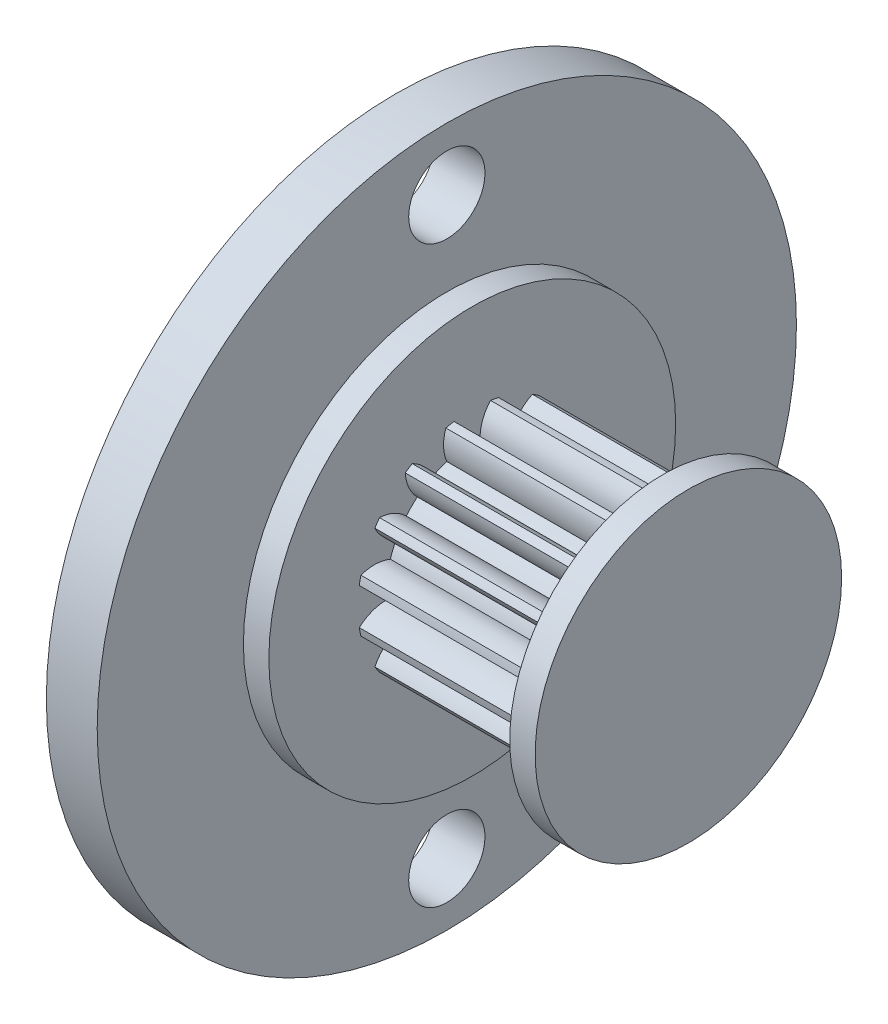
SolidWorks part; units mm, degrees
ref_plane "Plane1" through (0, 0, 0) normal (0, 0, 1) x (1, 0, 0)
ref_plane "Plane2" through (0, 0, 0) normal (0, 1, 0) x (1, 0, 0)
ref_plane "Plane3" through (0, 0, 0) normal (1, 0, 0) x (0, 0, -1)
sketch "HoldingSke" plane through (0, 0, 0) normal (0, 1, 0) x (1, 0, 0)
  line L0 (0, 0) -> (1.9225, -0.5513)
  line L1 (-15, 0) -> (100, 0) construction
  line L2 (0, 0) -> (-2.1039, 2.3779)
  line L3 (0, 0) -> (-11.863, 4.5341)
  line L4 (0, 0) -> (8.3015, 2.3804)
  line L5 (0, 0) -> (-46.8476, -17.4728)
  line L6 (0, 0) -> (-6.2172, -4.1948)
  line L7 (-2.1039, 2.3779) -> (8.6586, 51.2059)
  line L8 (-76.2, 54.61) -> (-75.3, 54.61)
  line L9 (-67.7845, 28.3722) -> (-49.3413, 33.142)
  line L10 (-76.2, 71.12) -> (104.1128, 71.12)
  line L11 (0, 0) -> (-7.5, 0)
  line L12 (-76.2, 101.6) -> (-76.181, 101.6)
  line L13 (24.9733, 27.94) -> (52.9518, 28.4284)
  line L14 (24.9733, 27.94) -> (24.9743, 27.94)
  line L15 (24.9733, 27.94) -> (100.4006, 29.5858)
  line L16 (-63.627, -0.5) -> (-12.827, -0.5)
  circle A0 centre (0, 0) radius 2.5
  circle A1 centre (0, 0) radius 3.374
  circle A2 centre (0, 0) radius 37.5
  circle A3 centre (0, 0) radius 2.5
  dimension "MHD" = 6.748
  dimension "Hub_dia" = 75
  dimension "Bore" = 5
  dimension "MBD" = 5
  dimension "Num_teeth" = 16
  dimension "Pitch" = 2
  dimension "Overall_len" = 50
  dimension "Show_teeth" = 16
  dimension "Thickness" = 7.5
  dimension "OAL" = 50.0001
  dimension "T_dim" = 0.9
  dimension "Ap" = 14.5
  dimension "H" = 19.05
  dimension "Pitch_radius" = 180.3128
  dimension "Width" = 7.5
  dimension "Backlash" = 0.019
  dimension "Addendum_fac" = 1
  dimension "Dedendum_fac" = 1.25
  dimension "Clearance_fac" = 0.25
  dimension "Dedendum_add" = 0.001
  dimension "Module" = 0.5
sketch "BasProSke" plane through (0, 0, 0) normal (0, 1, 0) x (1, 0, 0)
  line L0 (-10, 0) -> (60, 0) construction
  line L1 (0, 0) -> (0, 4.5)
  line L2 (0, 0) -> (7.5, 0)
  line L3 (7.5, 0) -> (7.5, 4.5)
  line L4 (7.5, 4.5) -> (0, 4.5)
  dimension "Thickness" = 7.5
  dimension "Diameter" = 9
revolve "Base-Revolve" add sketch "BasProSke" angle 360 about L0
sketch "TooCutSke" plane through (0, 0, 0) normal (1, 0, 0) x (0, 0, -1)
  line L1 (0, 0) -> (0, 107) construction
  line L2 (0, 0) -> (-0.4253, 3.9773) construction
  line L3 (0, 0) -> (-1.5544, 7.8146) construction
  line L4 (-0.4253, 3.9773) -> (-0.7772, 3.9073) construction
  arc A0 (0.306, 3.3601) -> (-0.306, 3.3601) centre (0, 0) ccw
  arc A1 (0.7382, 4.4648) -> (-0.7382, 4.4648) centre (0, 0) ccw
  circle A2 centre (0, 0) radius 4 construction
  circle A3 centre (0, 0) radius 3.8726 construction
  arc A4 (-0.306, 3.3601) -> (-0.7382, 4.4648) centre (-1.906, 3.3711) ccw
  arc A5 (0.7382, 4.4648) -> (0.306, 3.3601) centre (1.906, 3.3711) ccw
  dimension "Root_dia" = 6.748
  dimension "Overcut_dia" = 9.0508
  dimension "Pitch_dia" = 8
  dimension "Base_dia" = 7.7452
  dimension "Flank_rad" = 1.6
  dimension "Half_ang" = 11.25
  dimension "Half_CT" = 0.3588
extrude "ToothCut" cut sketch "TooCutSke" along normal through all
fillet "Breaks" [suppressed] radius 0.01
fillet "RootFillets" [suppressed] radius 0.126
pattern_circular "TeethCuts" count 16 every 22.5 about axis through (-10, 0, 0) along (1, 0, 0) of "ToothCut", "RootFillets", "Breaks"
sketch "HubNeaOneSke" plane through (0, 0, 0) normal (-1, 0, 0) x (0, 0, 1)
  circle A0 centre (0, 0) radius 3.374
  dimension "Diameter" = 6.748
extrude "HubNearOne" [suppressed] add sketch "HubNeaOneSke" along normal blind 42.5001
sketch "HubNeaBotSke" plane through (0, 0, 0) normal (-1, 0, 0) x (0, 0, 1)
  circle A0 centre (0, 0) radius 3.374
  dimension "Diameter" = 6.748
extrude "HubNearBoth" [suppressed] add sketch "HubNeaBotSke" along normal blind 21.25
ref_plane "FarPln" through (7.5, 0, 0) normal (1, 0, 0) x (0, 0, -1)
sketch "HubFarSke" plane through (7.5, 0, 0) normal (1, 0, 0) x (0, 0, -1)
  circle A0 centre (0, 0) radius 3.374
  dimension "Diameter" = 6.748
extrude "HubFar" [suppressed] add sketch "HubFarSke" along normal blind 21.25
sketch "BorSke" plane through (0, 0, 0) normal (1, 0, 0) x (0, 0, -1)
  circle A0 centre (0, 0) radius 2.5
  dimension "Diameter" = 5
extrude "Bore" cut sketch "BorSke" along normal mid plane 100.0001
sketch "KeySke" plane through (0, 0, 0) normal (1, 0, 0) x (0, 0, -1)
  line L0 (-1, 0) -> (-1, 3.4)
  line L1 (-1, 3.4) -> (1, 3.4)
  line L2 (1, 3.4) -> (1, 0)
  line L3 (0, 0) -> (0, 34) construction
  line L4 (-1, 0) -> (1, 0)
  dimension "Offset" = 3.4
  dimension "Width" = 2
extrude "Keyway" [suppressed] cut sketch "KeySke" along normal mid plane 100.0001
pattern_circular "Keyway2" [suppressed] count 2 every 90 about axis through (-10, 0, 0) along (1, 0, 0)
sketch "Esquisse4" plane through (0, 0, 0) normal (-1, 0, 0) x (0, 0, 1)
  circle A1 centre (0, 0) radius 6
  dimension "D1" = 12
extrude "Boss.-Extru.3" add sketch "Esquisse4" along normal blind 1
sketch "Esquisse5" plane through (7.5, 0, 0) normal (1, 0, 0) x (0, 0, -1)
  circle A0 centre (0, 0) radius 2.85
  circle A1 centre (0, 0) radius 6.0278
extrude "Boss.-Extru.4" add sketch "Esquisse5" along normal blind 1
sketch "Esquisse7" plane through (0, 0, 0) normal (1, 0, 0) x (0, 0, -1)
  circle A0 centre (0, 0) radius 3.0071
extrude "Boss.-Extru.6" add sketch "Esquisse7" along normal up to surface (8.5 mm away) up to face at (8.5, 0, -6.0278)
sketch "Esquisse9" plane through (-1, 0, 0) normal (-1, 0, 0) x (0, 0, 1)
  circle A0 centre (0, 0) radius 13.75
  circle A1 centre (0, 0) radius 5.5
  dimension "D1" = 27.5
  dimension "D2" = 11
extrude "Boss.-Extru.8" add sketch "Esquisse9" along normal blind 2
sketch "Esquisse10" plane through (-3, 0, 0) normal (-1, 0, 0) x (0, 0, 1)
  line L0 (-13.75, 0) -> (13.75, 0) construction
  line L1 (0, 13.75) -> (0, -13.75) construction
  circle A0 centre (0, 11.3) radius 1.5
  circle A1 centre (0, -11.3) radius 1.5
  circle A2 centre (0, 0) radius 13.75 construction
  dimension "D1" = 0
  dimension "D2" = 3
  dimension "D3" = 11.3
  dimension "D4" = 3
  dimension "D5" = 11.3
  dimension "D6" = 0
extrude "Enlèv. mat.-Extru.3" cut sketch "Esquisse10" against normal through all
sketch "Esquisse11" plane through (-1, 0, 0) normal (-1, 0, 0) x (0, 0, 1)
  circle A0 centre (0, 0) radius 3
  dimension "D1" = 6
extrude "Enlèv. mat.-Extru.4" cut sketch "Esquisse11" against normal blind 4
sketch "Esquisse12" plane through (3, 0, 0) normal (-1, 0, 0) x (0, 0, 1)
  circle A0 centre (0, 0) radius 3
extrude "Boss.-Extru.9" add sketch "Esquisse12" along normal up to surface (4 mm away) up to face at (-1, 0, 3)
sketch "Esquisse13" plane through (-1, 0, 0) normal (-1, 0, 0) x (0, 0, 1)
  circle A0 centre (0, 0) radius 5.5
extrude "Boss.-Extru.10" add sketch "Esquisse13" along normal up to surface (2 mm away) up to face at (-3, 11.3, 1.5)
sketch "Esquisse16" plane through (-1, 0, 0) normal (1, 0, 0) x (0, 0, -1)
  circle A0 centre (0, 0) radius 8
  dimension "D1" = 16
extrude "Boss.-Extru.11" add sketch "Esquisse16" along normal up to surface (1 mm away) up to face at (0, 0, 6)
sketch "Esquisse14" plane through (-3, 0, 0) normal (-1, 0, 0) x (0, 0, 1)
  circle A0 centre (0, 0) radius 6
  dimension "D1" = 12
extrude "Enlèv. mat.-Extru.5" cut sketch "Esquisse14" against normal blind 1.5
sketch "Esquisse15" plane through (-1.5, 0, 0) normal (-1, 0, 0) x (0, 0, 1)
  circle A0 centre (0, 0) radius 3.25
  dimension "D1" = 6.5
extrude "Enlèv. mat.-Extru.6" cut sketch "Esquisse15" against normal blind 4.5
equation "' \"Module@HoldingSke\" = 6.35"
equation "' \"Num_teeth@HoldingSke\" = 12"
equation "' \"Ap@HoldingSke\" =  20"
equation "' \"Ap@HoldingSke\" = 20"
equation "' \"Width@HoldingSke\" = 0.5 * 25.4"
equation "' \"Hub_dia@HoldingSke\"= 1 * 25.4"
equation "' \"Hub_dia@HoldingSke\" = 1 * 25.4"
equation "' \"Overall_len@HoldingSke\" = 1.0 * 25.4"
equation "' \"Bore@HoldingSke\" = 0.75 * 25.4"
equation "' \"T_dim@HoldingSke\" = 0.1 * 25.4"
equation "' \"Width@KeySke\" = 0.25 * 25.4"
equation "' \"Show_teeth@HoldingSke\" = 13"
equation "' \"Backlash@HoldingSke\" = 0.009 * 25.4"
equation "' \"Addendum_fac@HoldingSke\" = 1.0"
equation "' \"Dedendum_fac@HoldingSke\" = 1.25"
equation "' \"Dedendum_add@HoldingSke\" = 0.00005 * 25.4"
equation "' \"Clearance_fac@HoldingSke\" = 0.25"
equation "\"Pitch@HoldingSke\" = 1 / \"Module@HoldingSke\""
equation "\"Overcut_dia@TooCutSke\" = (\"Num_teeth@HoldingSke\" + 2 * \"Addendum_fac@HoldingSke\") / \"Pitch@HoldingSke\" + 0.002 * 25.4"
equation "\"Pitch_dia@TooCutSke\" = \"Num_teeth@HoldingSke\" / \"Pitch@HoldingSke\""
equation "\"Base_dia@TooCutSke\" = \"Num_teeth@HoldingSke\" / \"Pitch@HoldingSke\" * cos((\"Ap@HoldingSke\"  * 3.14159265 / 180))"
equation "\"Root_dia@TooCutSke\" = (\"Num_teeth@HoldingSke\" + 2) / \"Pitch@HoldingSke\" - 2 * (\"Addendum_fac@HoldingSke\" + \"Dedendum_fac@HoldingSke\") / \"Pitch@HoldingSke\" - \"Dedendum_add@HoldingSke\" * 2"
equation "\"Half_ang@TooCutSke\" = 180 / \"Num_teeth@HoldingSke\""
equation "\"Half_CT@TooCutSke\" = \"Num_teeth@HoldingSke\" / \"Pitch@HoldingSke\" * sin((3.14159265 / 2 / \"Num_teeth@HoldingSke\")) / 2 - 7 * \"Backlash@HoldingSke\" / 4"
equation "\"Flank_rad@TooCutSke\" = \"Num_teeth@HoldingSke\" / \"Pitch@HoldingSke\" / 5"
equation "\"Radius@RootFillets\" = \"Clearance_fac@HoldingSke\" / \"Pitch@HoldingSke\" + \"Dedendum_add@HoldingSke\""
equation "\"Break_rad@Breaks\" = 0.02 / \"Pitch@HoldingSke\""
equation "\"Thickness@HoldingSke\" = \"Width@HoldingSke\""
equation "\"OAL@HoldingSke\" = \"Thickness@HoldingSke\""
equation "\"MHD@HoldingSke\" = (\"Num_teeth@HoldingSke\" + 2) / \"Pitch@HoldingSke\" - 2 * (\"Addendum_fac@HoldingSke\" + \"Dedendum_fac@HoldingSke\")  / \"Pitch@HoldingSke\" - \"Dedendum_add@HoldingSke\" * 2"
equation "\"MBD@HoldingSke\" = (\"Num_teeth@HoldingSke\" + 2) / \"Pitch@HoldingSke\" - 2 * (\"Addendum_fac@HoldingSke\" + \"Dedendum_fac@HoldingSke\")  / \"Pitch@HoldingSke\" - \"Dedendum_add@HoldingSke\" * 2 - 0.002 * 25.4"
equation "\"MHD@HoldingSke\" = ((sgn( \"MHD@HoldingSke\" - \"Hub_dia@HoldingSke\" )-1)*( \"MHD@HoldingSke\" - \"Hub_dia@HoldingSke\" ))/-2+ \"Hub_dia@HoldingSke\""
equation "\"MBD@HoldingSke\" = ((sgn( \"MBD@HoldingSke\" - \"Bore@HoldingSke\" )-1)*( \"MBD@HoldingSke\" - \"Bore@HoldingSke\" ))/-2+ \"Bore@HoldingSke\""
equation "\"OAL@HoldingSke\" = ((sgn( \"OAL@HoldingSke\" - \"Overall_len@HoldingSke\" )+1)*( \"OAL@HoldingSke\" - \"Overall_len@HoldingSke\" ))/2 + \"Overall_len@HoldingSke\" + 0.000002 * 25.4"
equation "\"Num_teeth@TeethCuts\" = int( \"Show_teeth@HoldingSke\" ) + 1"
equation "\"Num_teeth@TeethCuts\" = ((sgn( \"Num_teeth@TeethCuts\" - \"Num_teeth@HoldingSke\" )-1)*( \"Num_teeth@TeethCuts\" - \"Num_teeth@HoldingSke\" ))/-2+ \"Num_teeth@HoldingSke\""
equation "\"Num_teeth@TeethCuts\" = ((sgn( \"Num_teeth@TeethCuts\" - 2.0)+1)*( \"Num_teeth@TeethCuts\" - 2.0))/2 +2.0"
equation "\"Angle@TeethCuts\" = 360.0 / \"Num_teeth@HoldingSke\""
equation "\"Diameter@BasProSke\" = (\"Num_teeth@HoldingSke\" + 2 * \"Addendum_fac@HoldingSke\") / \"Pitch@HoldingSke\""
equation "\"Thickness@BasProSke\"  = \"Thickness@HoldingSke\""
equation "' \"Fillet_rad@BasProSke\" =  \"Thickness@HoldingSke\" * 0.05"
equation "' \"Fillet_rad@BasProSke\" = \"Thickness@HoldingSke\" * 0.05"
equation "\"MHD@HoldingSke\" = ((sgn( \"MHD@HoldingSke\" - \"Root_dia@TooCutSke\" )-1)*( \"MHD@HoldingSke\" - \"Root_dia@TooCutSke\" ))/-2+ \"Root_dia@TooCutSke\""
equation "\"Diameter@HubNeaOneSke\" = \"MHD@HoldingSke\""
equation "\"Length@HubNearOne\" = \"OAL@HoldingSke\" - \"Thickness@BasProSke\""
equation "\"Diameter@HubNeaBotSke\" = \"MHD@HoldingSke\""
equation "\"Length@HubNearBoth\" = ( \"OAL@HoldingSke\" - \"Thickness@BasProSke\" ) / 2.0"
equation "\"Thickness@FarPln\" = \"Thickness@BasProSke\""
equation "\"Diameter@HubFarSke\" = \"MHD@HoldingSke\""
equation "\"Length@HubFar\" = ( \"OAL@HoldingSke\" - \"Thickness@BasProSke\" ) / 2.0"
equation "\"Diameter@BorSke\" = \"MBD@HoldingSke\""
equation "\"D1@Bore\" = \"OAL@HoldingSke\" * 2.0"
equation "\"D1@Keyway\" = \"OAL@HoldingSke\" * 2.0"
equation "\"Offset@KeySke\" = \"T_dim@HoldingSke\" + \"MBD@HoldingSke\" / 2.0"
